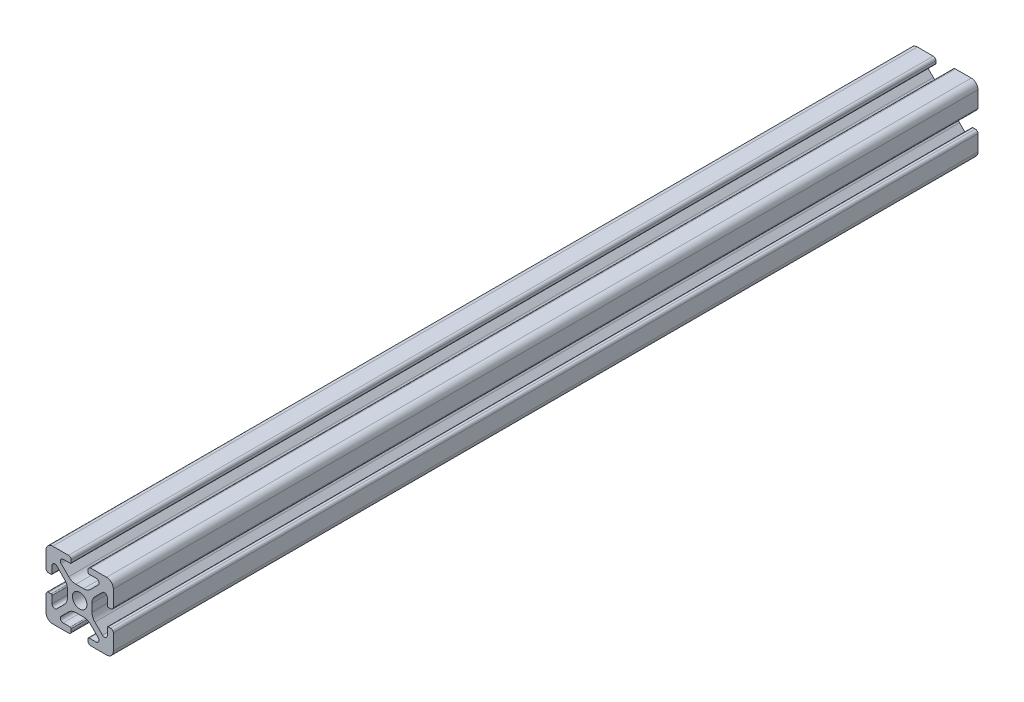
SolidWorks part; units mm, degrees
material "Alliage 1060"
ref_plane "Plan de face" through (0, 0, 0) normal (0, 0, 1) x (1, 0, 0)
ref_plane "Plan de dessus" through (0, 0, 0) normal (0, 1, 0) x (1, 0, 0)
ref_plane "Plan de droite" through (0, 0, 0) normal (1, 0, 0) x (0, 0, -1)
sketch "Esquisse1" plane through (0, 0, 0) normal (0, 0, 1) x (1, 0, 0)
  line L108 (-3.2559, 4.5287) -> (-5.5062, 6.779)
  line L109 (-4.9176, 8.2) -> (-2.8, 8.2)
  line L110 (-2.5, 8.5) -> (-2.5, 9.2)
  line L111 (-3.3, 10) -> (-8, 10)
  line L112 (-10, 8) -> (-10, 3.3)
  line L113 (-9.2, 2.5) -> (-8.5, 2.5)
  line L114 (-8.2, 2.8) -> (-8.2, 4.9176)
  line L115 (-6.779, 5.5062) -> (-4.5287, 3.2559)
  line L116 (-3.65, 1.1346) -> (-3.65, -1.1346)
  line L117 (-4.5287, -3.2559) -> (-6.779, -5.5062)
  line L118 (-8.2, -4.9176) -> (-8.2, -2.8)
  line L119 (-8.5, -2.5) -> (-9.2, -2.5)
  line L120 (-10, -3.3) -> (-10, -8)
  line L121 (-8, -10) -> (-3.3, -10)
  line L122 (-2.5, -9.2) -> (-2.5, -8.5)
  line L123 (-2.8, -8.2) -> (-4.9176, -8.2)
  line L124 (-5.5062, -6.779) -> (-3.2559, -4.5287)
  line L125 (-1.1346, -3.65) -> (1.1346, -3.65)
  line L126 (3.2559, -4.5287) -> (5.5062, -6.779)
  line L127 (4.9176, -8.2) -> (2.8, -8.2)
  line L128 (2.5, -8.5) -> (2.5, -9.2)
  line L129 (3.3, -10) -> (8, -10)
  line L130 (10, -8) -> (10, -3.3)
  line L131 (9.2, -2.5) -> (8.5, -2.5)
  line L132 (8.2, -2.8) -> (8.2, -4.9176)
  line L133 (6.779, -5.5062) -> (4.5287, -3.2559)
  line L134 (3.65, -1.1346) -> (3.65, 1.1346)
  line L135 (4.5287, 3.2559) -> (6.779, 5.5062)
  line L136 (8.2, 4.9176) -> (8.2, 2.8)
  line L137 (8.5, 2.5) -> (9.2, 2.5)
  line L138 (10, 3.3) -> (10, 8)
  line L139 (8, 10) -> (3.3, 10)
  line L140 (2.5, 9.2) -> (2.5, 8.5)
  line L141 (2.8, 8.2) -> (4.9176, 8.2)
  line L142 (5.5062, 6.779) -> (3.2559, 4.5287)
  line L143 (1.1346, 3.65) -> (-1.1346, 3.65)
  arc A42 (-2.15, 0) -> (2.15, 0) centre (0, 0) ccw
  arc A43 (2.15, 0) -> (-2.15, 0) centre (0, 0) ccw
  arc A108 (-4.9176, 8.2) -> (-5.5062, 6.779) centre (-4.9176, 7.3676) ccw
  arc A109 (-2.8, 8.2) -> (-2.5, 8.5) centre (-2.8, 8.5) ccw
  arc A110 (-2.5, 9.2) -> (-3.3, 10) centre (-3.3, 9.2) ccw
  arc A111 (-8, 10) -> (-10, 8) centre (-8, 8) ccw
  arc A112 (-10, 3.3) -> (-9.2, 2.5) centre (-9.2, 3.3) ccw
  arc A113 (-8.5, 2.5) -> (-8.2, 2.8) centre (-8.5, 2.8) ccw
  arc A114 (-6.779, 5.5062) -> (-8.2, 4.9176) centre (-7.3676, 4.9176) ccw
  arc A115 (-3.65, 1.1346) -> (-4.5287, 3.2559) centre (-6.65, 1.1346) ccw
  arc A116 (-4.5287, -3.2559) -> (-3.65, -1.1346) centre (-6.65, -1.1346) ccw
  arc A117 (-8.2, -4.9176) -> (-6.779, -5.5062) centre (-7.3676, -4.9176) ccw
  arc A118 (-8.2, -2.8) -> (-8.5, -2.5) centre (-8.5, -2.8) ccw
  arc A119 (-9.2, -2.5) -> (-10, -3.3) centre (-9.2, -3.3) ccw
  arc A120 (-10, -8) -> (-8, -10) centre (-8, -8) ccw
  arc A121 (-3.3, -10) -> (-2.5, -9.2) centre (-3.3, -9.2) ccw
  arc A122 (-2.5, -8.5) -> (-2.8, -8.2) centre (-2.8, -8.5) ccw
  arc A123 (-5.5062, -6.779) -> (-4.9176, -8.2) centre (-4.9176, -7.3676) ccw
  arc A124 (-1.1346, -3.65) -> (-3.2559, -4.5287) centre (-1.1346, -6.65) ccw
  arc A125 (3.2559, -4.5287) -> (1.1346, -3.65) centre (1.1346, -6.65) ccw
  arc A126 (4.9176, -8.2) -> (5.5062, -6.779) centre (4.9176, -7.3676) ccw
  arc A127 (2.8, -8.2) -> (2.5, -8.5) centre (2.8, -8.5) ccw
  arc A128 (2.5, -9.2) -> (3.3, -10) centre (3.3, -9.2) ccw
  arc A129 (8, -10) -> (10, -8) centre (8, -8) ccw
  arc A130 (10, -3.3) -> (9.2, -2.5) centre (9.2, -3.3) ccw
  arc A131 (8.5, -2.5) -> (8.2, -2.8) centre (8.5, -2.8) ccw
  arc A132 (6.779, -5.5062) -> (8.2, -4.9176) centre (7.3676, -4.9176) ccw
  arc A133 (3.65, -1.1346) -> (4.5287, -3.2559) centre (6.65, -1.1346) ccw
  arc A134 (4.5287, 3.2559) -> (3.65, 1.1346) centre (6.65, 1.1346) ccw
  arc A135 (8.2, 4.9176) -> (6.779, 5.5062) centre (7.3676, 4.9176) ccw
  arc A136 (8.2, 2.8) -> (8.5, 2.5) centre (8.5, 2.8) ccw
  arc A137 (9.2, 2.5) -> (10, 3.3) centre (9.2, 3.3) ccw
  arc A138 (10, 8) -> (8, 10) centre (8, 8) ccw
  arc A139 (3.3, 10) -> (2.5, 9.2) centre (3.3, 9.2) ccw
  arc A140 (2.5, 8.5) -> (2.8, 8.2) centre (2.8, 8.5) ccw
  arc A141 (5.5062, 6.779) -> (4.9176, 8.2) centre (4.9176, 7.3676) ccw
  arc A142 (1.1346, 3.65) -> (3.2559, 4.5287) centre (1.1346, 6.65) ccw
  arc A143 (-3.2559, 4.5287) -> (-1.1346, 3.65) centre (-1.1346, 6.65) ccw
extrude "Boss.-Extru.1" add sketch "Esquisse1" along normal blind 256.86
